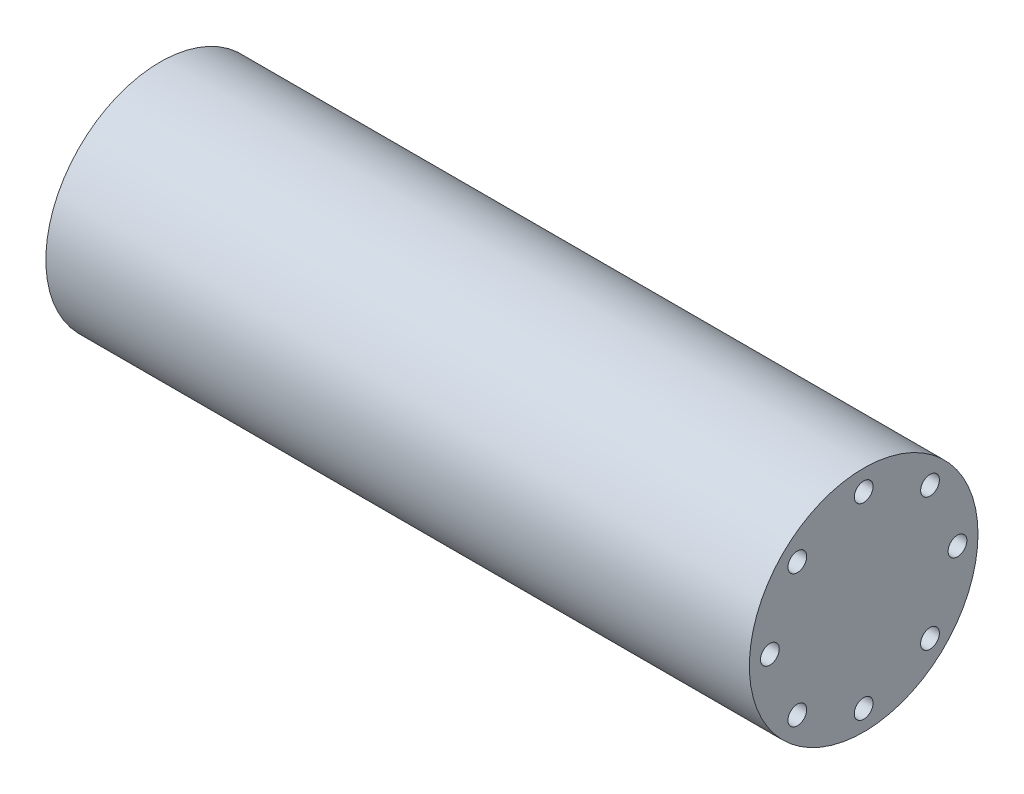
SolidWorks part; units mm, degrees
ref_plane "정면" through (0, 0, 0) normal (0, 0, 1) x (1, 0, 0)
ref_plane "윗면" through (0, 0, 0) normal (0, 1, 0) x (1, 0, 0)
ref_plane "우측면" through (0, 0, 0) normal (1, 0, 0) x (0, 0, -1)
sketch "Sketch1" plane through (0, 0, 0) normal (1, 0, 0) x (0, 0, -1)
  circle A0 centre (0, 0) radius 9.75
  dimension "D1" = 19.5
extrude "Boss-Extrude1" add sketch "Sketch1" along normal blind 60
sketch "Sketch2" plane through (60, 0, 0) normal (1, 0, 0) x (0, 0, -1)
  circle A0 centre (0, 0) radius 8 construction
  point P3 (0, 8)
  point P6 (5.6569, 5.6569)
  point P7 (8, 0)
  point P8 (5.6569, -5.6569)
  point P9 (0, -8)
  point P10 (-5.6569, -5.6569)
  point P11 (-8, 0)
  point P12 (-5.6569, 5.6569)
  point P13 (0, 0)
  dimension "D1" = 8
  dimension "D2" = 16
hole_wizard "M2 Tapped Hole1" positions "3DSketch2" profile "Sketch4" tap size "M2" standard "KS"
sketch3d "3DSketch2"
  point P0 (60, 8, 0)
  point P3 (60, 5.6569, -5.6569)
  point P6 (60, 0, -8)
  point P9 (60, -5.6569, -5.6569)
  point P12 (60, -8, 0)
  point P15 (60, -5.6569, 5.6569)
  point P18 (60, 0, 8)
  point P21 (60, 5.6569, 5.6569)
sketch "Sketch4" plane through (60, 8, 0) normal (0, 1, 0) x (0, 0, -1)
  line L0 (0, 0) -> (0, 5.6807)
  line L1 (0, 5.6807) -> (0.8, 5.2)
  line L2 (0.8, 5.2) -> (0.8, 0)
  line L5 (0.8, 0) -> (0, 0)
  line L10 (0, 5.6807) -> (-0.8, 5.2) construction
  line L11 (0, -6.35) -> (0, 107.95) construction
  dimension "Tap Drill Dia." = 1.6
  dimension "Tap Drill Depth" = 5.2
  dimension "Drill Angle" = 118
cosmetic thread "Hole Thread1"
cosmetic thread "Hole Thread2"
cosmetic thread "Hole Thread3"
cosmetic thread "Hole Thread4"
cosmetic thread "Hole Thread5"
cosmetic thread "Hole Thread6"
cosmetic thread "Hole Thread7"
cosmetic thread "Hole Thread8"
ref_plane "Plane1" through (30, 0, 0) normal (1, 0, 0) x (0, 0, -1)
mirror "Mirror1" about plane through (30, 0, 0) normal (1, 0, 0) of "M2 Tapped Hole1"
cosmetic thread "Hole Thread9"
cosmetic thread "Hole Thread10"
cosmetic thread "Hole Thread11"
cosmetic thread "Hole Thread12"
cosmetic thread "Hole Thread13"
cosmetic thread "Hole Thread14"
cosmetic thread "Hole Thread15"
cosmetic thread "Hole Thread16"
